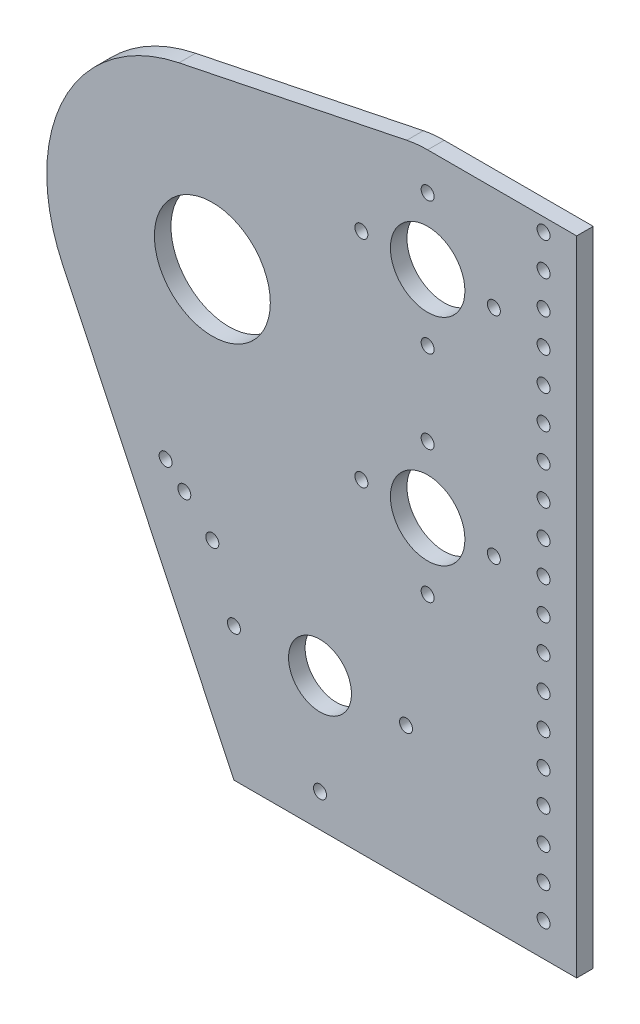
SolidWorks part; units mm, degrees
ref_plane "Front Plane" through (0, 0, 0) normal (1, 0, 0) x (0, 1, 0)
ref_plane "Top Plane" through (0, 0, 0) normal (0, 0, 1) x (0, 1, 0)
ref_plane "Right Plane" through (0, 0, 0) normal (0, 1, 0) x (-1, 0, 0)
sketch "Sketch1" plane through (0, 0, 0) normal (0, 0, 1) x (0, 1, 0)
  line L2 (80.9625, -82.55) -> (80.9625, -139.7)
  line L3 (80.9625, -139.7) -> (-165.481, -139.7)
  line L6 (62.2001, 12.7827) -> (80.1501, -74.5608)
  line L7 (-122.8156, -32.7282) -> (-44.819, 44.9834) construction
  line L8 (-165.481, -139.7) -> (-165.481, -8.2804)
  line L9 (-165.481, -8.2804) -> (-27.2371, 57.3619)
  circle A0 centre (0, 0) radius 22.225
  circle A1 centre (0, 0) radius 41.275 construction
  circle A2 centre (0, 0) radius 63.5 construction
  circle A3 centre (-41.275, -82.55) radius 14.2875
  circle A4 centre (41.275, -82.55) radius 14.2875
  circle A5 centre (-41.275, -82.55) radius 39.6875 construction
  circle A6 centre (41.275, -82.55) radius 39.6875 construction
  arc A9 (80.1501, -74.5608) -> (80.9625, -82.55) centre (41.275, -82.55) cw
  circle A10 centre (-114.3, -41.275) radius 12.065
  arc A13 (-27.2371, 57.3619) -> (62.2001, 12.7827) centre (0, 0) cw
  circle A14 centre (-114.3, -41.275) radius 32.258 construction
  point P9 (-41.275, 0)
  point P12 (41.275, 0)
  point P22 (0, 0)
  point P24 (-114.3, -8.2804)
  point P25 (-114.3, -74.2696)
  point P26 (-152.781, -41.275)
  point P27 (0, 0)
  point P28 (-114.3, -41.275)
  point P29 (-89.9674, 0)
  point P30 (-71.974, 17.9276)
  point P34 (-112.8014, -41.275)
  point P35 (-79.1714, 10.7566)
  point P36 (-80.9707, 8.9638)
  point P37 (0, -41.275)
  point P39 (0, 0)
  point P43 (0, 0)
  point P44 (0, 0)
  point P45 (0, 0)
  point P46 (-91.968, -1.9932)
  point P47 (0, 0)
  dimension "D1" = 44.45
  dimension "D2" = 19.05
  dimension "D3" = 127
  dimension "D4" = 28.575
  dimension "D6" = 25.4
  dimension "D7" = 139.7
  dimension "D12" = 24.13
  dimension "D17" = 12.7
  dimension "D18" = 64.516
  dimension "D5" = 82.55
  dimension "D8" = 1.4986
  dimension "D9" = 32.9946
  dimension "D10" = 32.9946
  dimension "D11" = 38.481
  dimension "D13" = 25.4
  dimension "D14" = 12.7
  dimension "D15" = 2.54
  dimension "D16" = 114.3
extrude "Boss-Extrude1" add sketch "Sketch1" along normal blind 6.35 contours A13 L6 A9 L2 L3 L8 L9
sketch "Sketch4" [suppressed] plane through (0, 0, 0) normal (1, 0, 0) x (0, 1, 0)
  line L2 (114.3, 80.9625) -> (114.3, -165.481) construction
  circle A0 centre (82.55, 41.275) radius 25.4 construction
  circle A1 centre (82.55, -41.275) radius 25.4 construction
  point P0 (82.55, -41.275)
  point P2 (82.55, 41.275)
  point P8 (57.15, 41.275)
  point P9 (82.55, 66.675)
  point P10 (107.95, 41.275)
  point P11 (82.55, 15.875)
  point P12 (82.55, -15.875)
  point P13 (57.15, -41.275)
  point P14 (82.55, -66.675)
  point P15 (107.95, -41.275)
  point P16 (127, -152.781)
  point P21 (127, -140.081)
  point P23 (127, -127.381)
  point P24 (127, -114.681)
  point P25 (127, -101.981)
  point P26 (127, -89.281)
  point P27 (127, -76.581)
  point P28 (127, -63.881)
  point P29 (127, -51.181)
  point P30 (127, -38.481)
  point P31 (127, -25.781)
  point P32 (127, -13.081)
  point P39 (-17.9276, -71.974)
  point P41 (-10.7566, -79.1714)
  point P43 (0, -89.9674)
  point P45 (41.275, -112.8014)
  point P47 (74.2696, -114.3)
  point P49 (41.275, -152.781)
  point P51 (8.2804, -114.3)
  point P61 (127, -0.381)
  point P62 (127, 12.319)
  point P63 (127, 25.019)
  point P64 (127, 37.719)
  point P65 (127, 50.419)
  point P66 (127, 63.119)
  point P67 (127, 75.819)
  point P68 (0, 0)
  dimension "D1" = 50.8
  dimension "D5" = 12.7
  dimension "D4" = 19
sketch "Sketch2" plane through (0, 0, 6.35) normal (0, 0, 1) x (1, 0, 0)
  line L1 (139.7, 80.9625) -> (139.7, -165.481) construction
  line L2 (114.3, 80.9625) -> (114.3, -165.481) construction
  line L3 (82.55, 80.9625) -> (139.7, 80.9625) construction
  line L6 (139.7, -165.481) -> (8.2804, -165.481) construction
  circle A0 centre (82.55, 41.275) radius 25.4 construction
  circle A1 centre (82.55, -41.275) radius 25.4 construction
  point P0 (82.55, -41.275)
  point P2 (82.55, 41.275)
  point P4 (82.55, 41.275)
  point P6 (82.55, -41.275)
  point P8 (57.15, 41.275)
  point P9 (82.55, 66.675)
  point P10 (107.95, 41.275)
  point P11 (82.55, 15.875)
  point P12 (82.55, -15.875)
  point P13 (57.15, -41.275)
  point P14 (82.55, -66.675)
  point P15 (107.95, -41.275)
  point P16 (127, -152.781)
  point P21 (127, -140.081)
  point P23 (127, -127.381)
  point P24 (127, -114.681)
  point P25 (127, -101.981)
  point P26 (127, -89.281)
  point P27 (127, -76.581)
  point P28 (127, -63.881)
  point P29 (127, -51.181)
  point P30 (127, -38.481)
  point P31 (127, -25.781)
  point P32 (127, -13.081)
  point P39 (-17.9276, -71.974)
  point P41 (-10.7566, -79.1714)
  point P43 (0, -89.9674)
  point P45 (41.275, -112.8014)
  point P47 (74.2696, -114.3)
  point P49 (41.275, -152.781)
  point P51 (8.2804, -114.3)
  point P61 (127, -0.381)
  point P62 (127, 12.319)
  point P63 (127, 25.019)
  point P64 (127, 37.719)
  point P65 (127, 50.419)
  point P66 (127, 63.119)
  point P67 (127, 75.819)
  dimension "D1" = 50.8
  dimension "D2" = 12.7
  dimension "D3" = 12.7
  dimension "D5" = 12.7
  dimension "D6" = 25.4
  dimension "D4" = 19
hole_wizard "#9 (0.196) Diameter Hole1" positions "Sketch2" profile "Sketch3" hole size "#9" standard "ANSI Inch" end condition through all
sketch "Sketch3" plane through (127, 75.819, 6.35) normal (1, 0, 0) x (0, -1, 0)
  line L0 (0, 0) -> (0, 6.35)
  line L1 (0, 6.35) -> (2.4892, 6.35)
  line L2 (2.4892, 6.35) -> (2.4892, 0)
  line L5 (2.4892, 0) -> (0, 0)
  line L11 (0, -6.35) -> (0, 107.95) construction
  dimension "Thru Hole Dia." = 4.9784
  dimension "Thru Hole Depth" = 6.35
